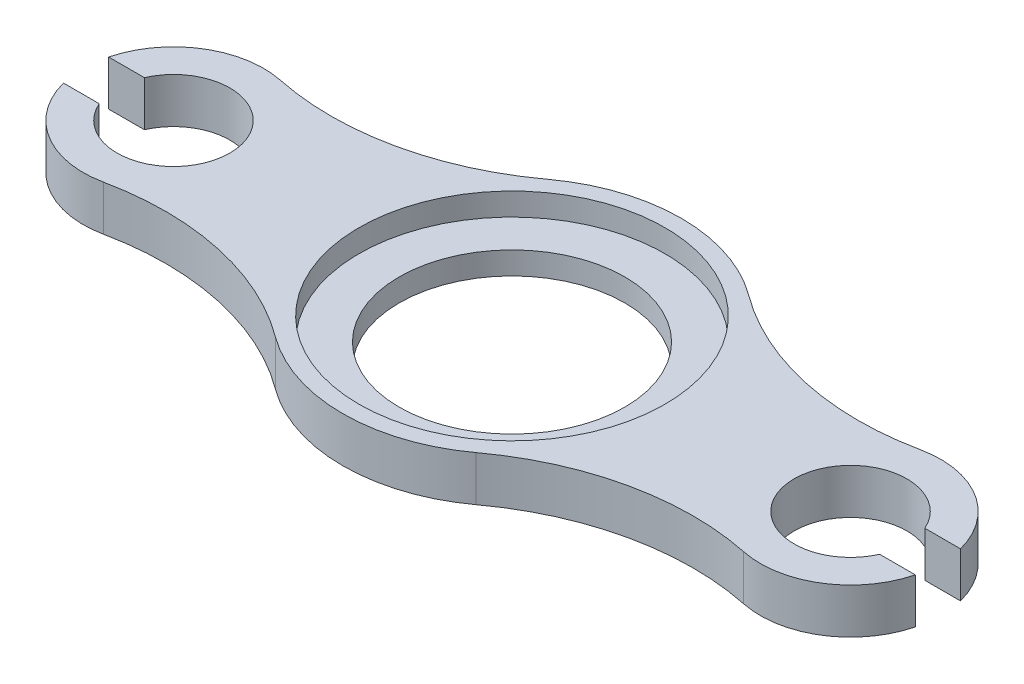
SolidWorks part; units mm, degrees
ref_plane "Ön Düzlem" through (0, 0, 0) normal (0, 0, 1) x (1, 0, 0)
ref_plane "Üst Düzlem" through (0, 0, 0) normal (0, 1, 0) x (1, 0, 0)
ref_plane "Sağ Düzlem" through (0, 0, 0) normal (1, 0, 0) x (0, 0, -1)
sketch "Çizim1" plane through (0, 0, 0) normal (0, 1, 0) x (1, 0, 0)
  line L4 (-188.7298, 10) -> (-172.9129, 10)
  line L5 (-188.7298, -10) -> (-172.9129, -10)
  line L6 (188.7298, -10) -> (172.9129, -10)
  line L7 (188.7298, 10) -> (172.9129, 10)
  circle A0 centre (0, 0) radius 50
  circle A1 centre (0, 0) radius 67.8
  circle A2 centre (0, 0) radius 75
  arc A3 (-172.9129, -10) -> (-172.9129, 10) centre (-150, 0) ccw
  arc A4 (-188.7298, -10) -> (-141.8254, -39.1558) centre (-150, 0) ccw
  arc A5 (172.9129, -10) -> (172.9129, 10) centre (150, 0) cw
  arc A6 (188.7298, -10) -> (141.8254, -39.1558) centre (150, 0) cw
  arc A7 (-141.8254, 39.1558) -> (-44.4958, 60.3749) centre (-116.8884, 158.6021) ccw
  arc A8 (-141.8254, -39.1558) -> (-44.4958, -60.3749) centre (-116.8884, -158.6021) cw
  arc A9 (141.8254, -39.1558) -> (44.4958, -60.3749) centre (116.8884, -158.6021) ccw
  arc A10 (141.8254, 39.1558) -> (44.4958, 60.3749) centre (116.8884, 158.6021) cw
  arc A11 (-141.8254, 39.1558) -> (-188.7298, 10) centre (-150, 0) ccw
  arc A12 (141.8254, 39.1558) -> (188.7298, 10) centre (150, 0) cw
  point P9 (0, 0)
  point P13 (0, 0)
  point P17 (0, 0)
  point P18 (0, 0)
  point P31 (0, 0)
  dimension "D1" = 100
  dimension "D2" = 135.6
  dimension "D3" = 150
  dimension "D4" = 50
  dimension "D5" = 80
  dimension "D6" = 50
  dimension "D7" = 80
  dimension "D8" = 150
  dimension "D9" = 150
extrude "Yükseklik-Ekstrüzyon4" add sketch "Çizim1" along normal blind 20 contours A7 A11 L4 A3 L5 A4 A8 A2 | A12 A10 A2 A9 A6 L6 A5 L7
sketch "Çizim5" plane through (0, 20, 0) normal (0, 1, 0) x (1, 0, 0)
  circle A0 centre (0, 0) radius 67.8
  circle A1 centre (0, 0) radius 50
  dimension "D1" = 100
  dimension "D2" = 135.6
extrude "Kes-Ekstrüzyon1" cut sketch "Çizim5" against normal blind 10
sketch "Çizim7" plane through (0, 20, 0) normal (0, 1, 0) x (1, 0, 0)
  circle A0 centre (0, 0) radius 50
  dimension "D1" = 100
extrude "Kes-Ekstrüzyon2" cut sketch "Çizim7" against normal blind 20
